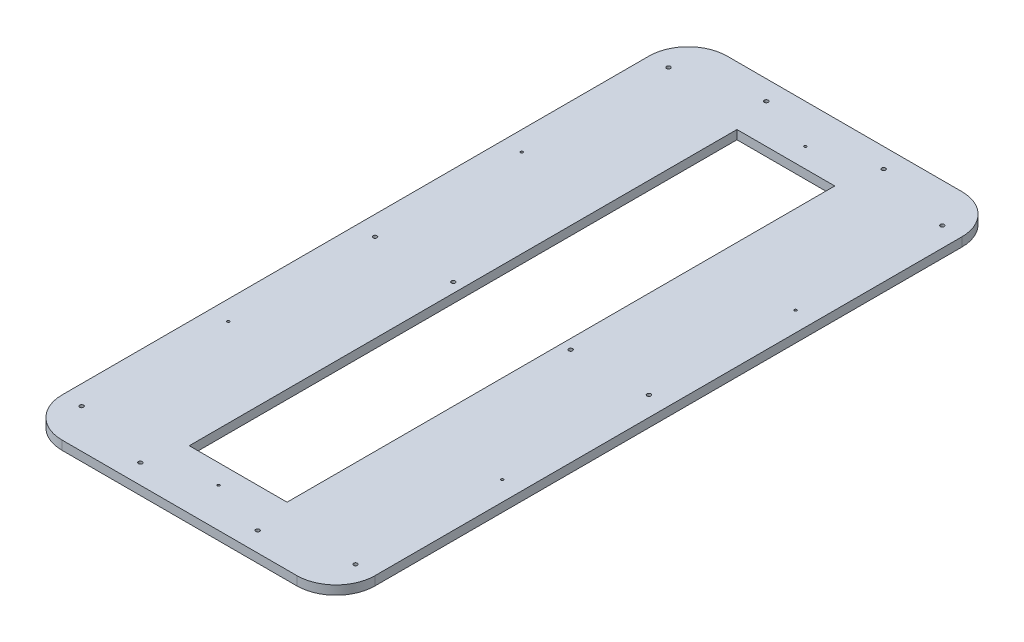
SolidWorks part; units mm, degrees
material "Acrylic (Medium-high impact)"
ref_plane "Front Plane" through (0, 0, 0) normal (0, 0, 1) x (1, 0, 0)
ref_plane "Top Plane" through (0, 0, 0) normal (0, 1, 0) x (1, 0, 0)
ref_plane "Right Plane" through (0, 0, 0) normal (1, 0, 0) x (0, 0, -1)
sketch "Sketch1" plane through (0, 0, 0) normal (0, 1, 0) x (1, 0, 0)
  line L1 (0, 0) -> (203.2, 0)
  line L2 (0, 0) -> (0, 431.8)
  line L3 (0, 431.8) -> (203.2, 431.8)
  line L4 (203.2, 0) -> (203.2, 431.8)
  dimension "D1" = 203.2
  dimension "D2" = 431.8
extrude "Boss-Extrude1" add sketch "Sketch1" along normal blind 5.8
hole_wizard "M3x0.5 Tapped Hole2" positions "Sketch6" profile "Sketch5" tap size "M3x0.5" standard "Ansi Metric"
sketch "Sketch6" plane through (0, 5.8, 0) normal (0, 1, 0) x (-1, 0, 0)
  line L4 (-101.6, 0) -> (-101.6, -431.8) construction
  line L8 (-63.5, -419.1) -> (-63.5, -12.7) construction
  line L10 (-139.7, -419.1) -> (-139.7, -12.7) construction
  line L15 (-63.5, -215.9) -> (-101.6, -215.9) construction
  line L16 (-101.6, -215.9) -> (-139.7, -215.9) construction
  line L19 (-203.2, -431.8) -> (0, -431.8) construction
  line L20 (-203.2, -431.8) -> (0, -431.8) construction
  line L21 (-63.5, -419.1) -> (-139.7, -419.1) construction
  line L24 (0, 0) -> (-203.2, 0) construction
  point P0 (-63.5, -419.1)
  point P1 (-139.7, -419.1)
  point P3 (-63.5, -215.9)
  point P5 (-139.7, -215.9)
  point P7 (-63.5, -12.7)
  point P9 (-139.7, -12.7)
  point P63 (-101.6, -431.8)
  dimension "D1" = 406.4
  dimension "D2" = 76.2
sketch "Sketch5" plane through (63.5, 5.8, -419.1) normal (1, 0, 0) x (0, 0, 1)
  line L0 (0, 0) -> (0, 8.2511)
  line L1 (0, 8.2511) -> (1.25, 7.5)
  line L2 (1.25, 7.5) -> (1.25, 0)
  line L5 (1.25, 0) -> (0, 0)
  line L10 (0, 8.2511) -> (-1.25, 7.5) construction
  line L11 (0, -6.35) -> (0, 107.95) construction
  dimension "Tap Drill Dia." = 2.5
  dimension "Tap Drill Depth" = 7.5
  dimension "Drill Angle" = 118
sketch "Sketch7" plane through (0, 5.8, 0) normal (0, 1, 0) x (1, 0, 0)
  line L0 (101.6, 38.1) -> (101.6, 0) construction
  line L1 (69.85, 393.7) -> (133.35, 393.7)
  line L2 (69.85, 393.7) -> (69.85, 38.1)
  line L3 (69.85, 38.1) -> (133.35, 38.1)
  line L4 (133.35, 393.7) -> (133.35, 38.1)
  line L5 (0, 0) -> (203.2, 0) construction
  line L6 (69.85, 215.9) -> (0, 215.9) construction
  line L8 (133.35, 215.9) -> (203.2, 215.9) construction
  line L10 (101.6, 393.7) -> (101.6, 431.8) construction
  line L11 (203.2, 431.8) -> (0, 431.8) construction
  line L12 (0, 431.8) -> (0, 0) construction
  line L13 (203.2, 0) -> (203.2, 431.8) construction
  dimension "D1" = 63.5
  dimension "D2" = 355.6
extrude "Cut-Extrude2" cut sketch "Sketch7" against normal through all
fillet "Fillet1" radius 25.4 4 edges at (203.2, 2.9, -431.8) (0, 2.9, -431.8) (203.2, 2.9, 0) (0, 2.9, 0)
hole_wizard "M3x0.5 Tapped Hole1" positions "Sketch9" profile "Sketch8" tap size "M3x0.5" standard "Ansi Metric"
sketch "Sketch9" plane through (0, 5.8, 0) normal (0, 1, 0) x (-1, 0, 0)
  line L0 (-190.5, -406.4) -> (-12.7, -406.4) construction
  line L1 (-12.7, -406.4) -> (-12.7, -25.4) construction
  line L2 (-12.7, -25.4) -> (-190.5, -25.4) construction
  line L3 (-190.5, -25.4) -> (-190.5, -406.4) construction
  line L5 (-101.6, -406.4) -> (-101.6, -431.8) construction
  line L6 (-177.8, -431.8) -> (-25.4, -431.8) construction
  line L8 (-101.6, -25.4) -> (-101.6, 0) construction
  line L9 (-25.4, 0) -> (-177.8, 0) construction
  point P0 (-190.5, -406.4)
  point P1 (-190.5, -25.4)
  point P3 (-12.7, -25.4)
  point P5 (-12.7, -406.4)
  point P27 (-190.5, -215.9)
  point P29 (-12.7, -215.9)
  dimension "D1" = 381
  dimension "D2" = 177.8
sketch "Sketch8" plane through (190.5, 5.8, -406.4) normal (1, 0, 0) x (0, 0, 1)
  line L0 (0, 0) -> (0, 8.2511)
  line L1 (0, 8.2511) -> (1.25, 7.5)
  line L2 (1.25, 7.5) -> (1.25, 0)
  line L5 (1.25, 0) -> (0, 0)
  line L10 (0, 8.2511) -> (-1.25, 7.5) construction
  line L11 (0, -6.35) -> (0, 107.95) construction
  dimension "Tap Drill Dia." = 2.5
  dimension "Tap Drill Depth" = 7.5
  dimension "Drill Angle" = 118
sketch "Sketch10" plane through (0, 5.8, 0) normal (0, 1, 0) x (1, 0, 0)
  line L1 (12.7, 406.4) -> (190.5, 406.4) construction
  line L2 (12.7, 406.4) -> (12.7, 215.9) construction
  line L3 (12.7, 215.9) -> (190.5, 215.9) construction
  line L4 (190.5, 406.4) -> (190.5, 215.9) construction
  circle A0 centre (12.7, 311.15) radius 0.7938
  circle A1 centre (190.5, 311.15) radius 0.7938
  circle A2 centre (101.6, 406.4) radius 0.7937
  circle A3 centre (101.6, 25.4) radius 0.7937
  circle A4 centre (190.5, 120.65) radius 0.7938
  circle A5 centre (12.7, 120.65) radius 0.7938
  dimension "D1" = 1.5875
extrude "Cut-Extrude3" cut sketch "Sketch10" against normal through all
